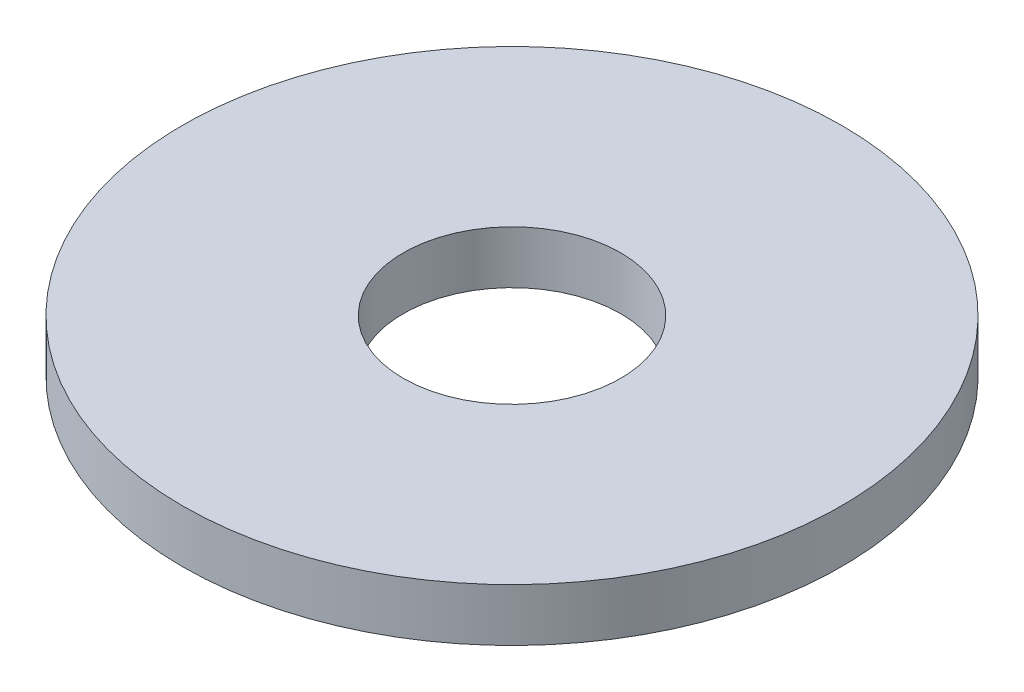
SolidWorks part; units mm, degrees
ref_plane "Спереди" through (0, 0, 0) normal (0, 0, 1) x (1, 0, 0)
ref_plane "Сверху" through (0, 0, 0) normal (0, 1, 0) x (1, 0, 0)
ref_plane "Справа" through (0, 0, 0) normal (1, 0, 0) x (0, 0, -1)
sketch "Эскиз1" plane through (0, 0, 0) normal (0, 1, 0) x (1, 0, 0)
  circle A0 centre (0, 0) radius 8.25
  circle A1 centre (0, 0) radius 25
  dimension "D1" = 50
  dimension "D2" = 16.5
extrude "Бобышка-Вытянуть1" add sketch "Эскиз1" along normal blind 4
